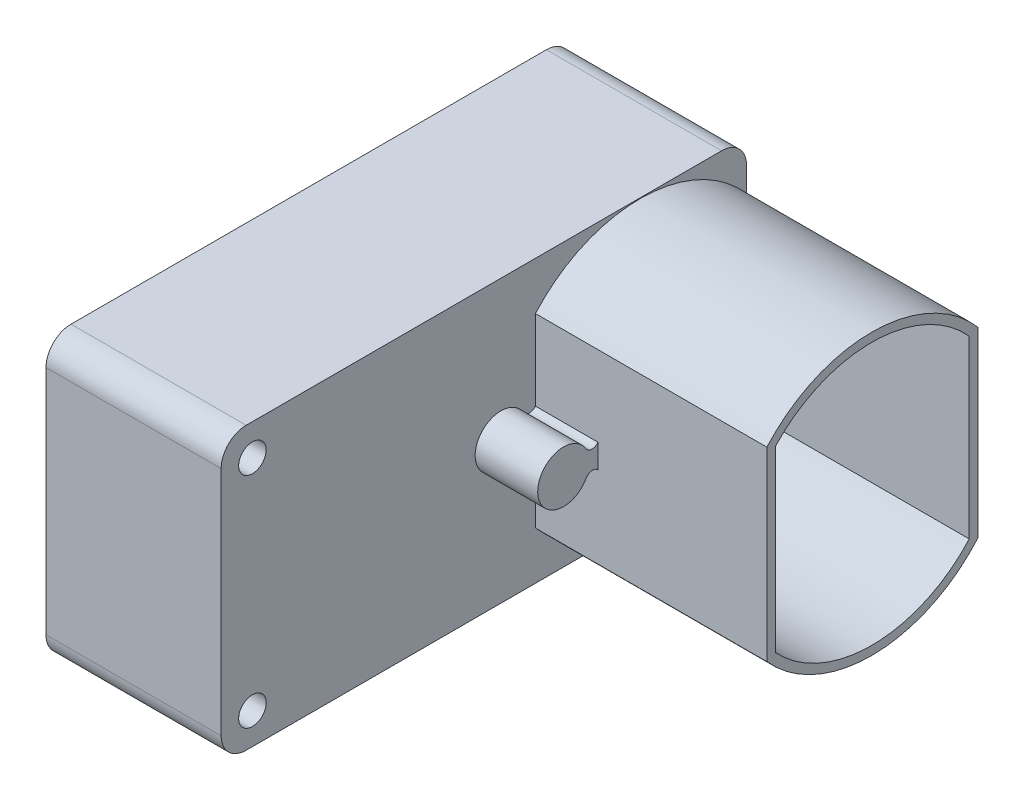
SolidWorks part; units mm, degrees
ref_plane "Front Plane" through (0, 0, 0) normal (0, 0, 1) x (1, 0, 0)
ref_plane "Top Plane" through (0, 0, 0) normal (0, 1, 0) x (1, 0, 0)
ref_plane "Right Plane" through (0, 0, 0) normal (1, 0, 0) x (0, 0, -1)
sketch "Sketch1" plane through (0, 0, 0) normal (0, 1, 0) x (1, 0, 0)
  line L1 (-21.7296, 20.5432) -> (-7.7296, 20.5432)
  line L2 (-21.7296, 20.5432) -> (-21.7296, -21.4568)
  line L3 (-21.7296, -21.4568) -> (-7.7296, -21.4568)
  line L4 (-7.7296, 20.5432) -> (-7.7296, -21.4568)
  dimension "D1" = 42
  dimension "D2" = 14
extrude "Boss-Extrude1" add sketch "Sketch1" along normal blind 22.5
fillet "Fillet1" radius 2 4 edges at (-14.7296, 22.5, -20.5432) (-14.7296, 0, -20.5432) (-14.7296, 0, 21.4568) (-14.7296, 22.5, 21.4568)
sketch "Sketch2" plane through (-7.7296, 0, 0) normal (1, 0, 0) x (0, 0, -1)
  line L0 (-19.4568, 0) -> (18.5432, 0) construction
  line L2 (3.6661, 18.6743) -> (3.6661, 3.8257)
  line L4 (20.5432, 18.5333) -> (20.5432, 3.9667)
  line L5 (20.5432, 20.5) -> (20.5432, 2) construction
  line L6 (-996.4568, 11.25) -> (49003.5432, 11.25) construction
  line L7 (12.0432, -977.25) -> (12.0432, 49022.75) construction
  arc A0 (20.5432, 18.5333) -> (3.6661, 18.6743) centre (12.0432, 11.25) ccw
  arc A1 (3.6661, 3.8257) -> (20.5432, 3.9667) centre (12.0432, 11.25) ccw
  point P11 (3.6661, 11.25)
  dimension "D1" = 11.25
extrude "Boss-Extrude2" add sketch "Sketch2" along normal blind 18.5
sketch "Sketch3" plane through (-7.7296, 0, 0) normal (1, 0, 0) x (0, 0, -1)
  line L0 (3.6661, 11.25) -> (-4.3884, 11.25) construction
  line L1 (3.6661, 18.6743) -> (3.6661, 3.8257) construction
  line L2 (3.6661, 18.6743) -> (3.6661, 3.8257) construction
  line L3 (3.6661, 12.2654) -> (3.6661, 10.3412)
  arc A0 (2.6785, 12.3299) -> (2.7239, 10.2481) centre (0.9148, 11.25) ccw
  arc A1 (2.6785, 12.3299) -> (3.6661, 12.2654) centre (3.1938, 12.6278) ccw
  arc A2 (2.7239, 10.2481) -> (3.6661, 10.3412) centre (3.2261, 9.9798) cw
  dimension "D1" = 2.7513
  dimension "D2" = 2.068
  dimension "D3" = 0.5953
  dimension "D4" = 0.5694
  dimension "D5" = 0.44
  dimension "D6" = 1.2702
  dimension "D7" = 1.3778
  dimension "D8" = 0.4723
extrude "Boss-Extrude3" add sketch "Sketch3" along normal blind 5
sketch "Sketch4" plane through (-7.7296, 0, 0) normal (1, 0, 0) x (0, 0, -1)
  line L0 (-18.9568, -979.1157) -> (-18.9568, 49020.8843) construction
  line L1 (-19.4568, 22.5) -> (18.5432, 22.5) construction
  line L2 (-21.4568, 20.5) -> (-21.4568, 2) construction
  line L3 (-19.4568, 0) -> (18.5432, 0) construction
  circle A0 centre (-18.9568, 20) radius 1.1
  circle A1 centre (-18.9568, 2.5) radius 1.1
  dimension "D1" = 2.5
  dimension "D2" = 2.5
  dimension "D3" = 2.5
extrude "Cut-Extrude1" cut sketch "Sketch4" against normal blind 15
sketch "Sketch5" plane through (0, 0, -20.5432) normal (0, 0, -1) x (-1, 0, 0)
  line L0 (7.7296, 18.5333) -> (7.7296, 3.9667) construction
  line L1 (21.7296, 0) -> (7.7296, 0) construction
  line L2 (6.7296, 9.25) -> (8.7296, 9.25)
  line L3 (6.7296, 9.25) -> (6.7296, 13.25)
  line L4 (6.7296, 13.25) -> (8.7296, 13.25)
  line L5 (8.7296, 9.25) -> (8.7296, 13.25)
  line L6 (6.7296, 9.25) -> (8.7296, 13.25) construction
  line L7 (6.7296, 13.25) -> (8.7296, 9.25) construction
  point P4 (7.7296, 11.25)
  dimension "D1" = 2
  dimension "D2" = 4
extrude "Boss-Extrude4" add sketch "Sketch5" along normal blind 5
sketch "Sketch6" plane through (-6.7296, 0, 0) normal (1, 0, 0) x (0, 0, -1)
  line L0 (25.5432, 13.25) -> (25.5432, 9.25) construction
  line L1 (20.5432, 3.9667) -> (20.5432, 18.5333) construction
  line L2 (20.5432, 13.25) -> (20.5432, 9.25) construction
  line L3 (25.5432, 9.25) -> (20.5432, 9.25) construction
  circle A0 centre (23.5432, 11.25) radius 2
  arc A1 (21.6793, 11.9753) -> (20.5432, 12.2253) centre (21.1327, 12.1978) cw
  arc A2 (21.6793, 10.5247) -> (20.5432, 10.7747) centre (21.0655, 10.4419) ccw
  line M1 (20.5432, 13.25) -> (20.5432, 9.25)
  dimension "D1" = 4
  dimension "D2" = 2
extrude "Boss-Extrude5" add sketch "Sketch6" along normal up to vertex (4 mm away) contours A0 A1 | A2 A0 A1 M1
sketch "Sketch7" plane through (-6.7296, 0, 0) normal (1, 0, 0) x (0, 0, -1)
  line L0 (23.5432, 13.25) -> (23.5432, 13.9672)
  line L1 (23.5432, 13.9672) -> (25.7602, 13.9672)
  line L2 (25.7602, 13.9672) -> (25.7602, 8.9705)
  line L3 (25.7602, 8.9705) -> (23.5432, 8.9705)
  line L4 (23.5432, 8.9705) -> (23.5432, 9.25)
  arc A0 (23.5432, 13.25) -> (23.5432, 9.25) centre (23.5432, 11.25) cw
  arc A1 (21.6793, 10.5247) -> (21.6793, 11.9753) centre (23.5432, 11.25) ccw construction
  arc A2 (23.5432, 9.25) -> (25.5432, 11.25) centre (23.5432, 11.25) ccw construction
extrude "Cut-Extrude2" cut sketch "Sketch7" against normal blind 2
sketch "Sketch12" plane through (-21.7296, 0, 0) normal (-1, 0, 0) x (0, 0, 1)
  line L0 (21.4568, 11.25) -> (10.4568, 11.25) construction
  line L1 (21.4568, 20.5) -> (21.4568, 2) construction
  circle A0 centre (10.4568, 11.25) radius 3.5
  circle A1 centre (10.4568, 11.25) radius 3.0703
extrude "Boss-Extrude6" add sketch "Sketch12" along normal blind 1
sketch "Sketch14" plane through (-21.7296, 0, 0) normal (-1, 0, 0) x (0, 0, 1)
  line L0 (-18.5432, 0) -> (19.4568, 0) construction
  line L2 (21.4568, 20.5) -> (21.4568, 2) construction
  circle A0 centre (10.4568, 11.25) radius 3
  dimension "D1" = 6
  dimension "D2" = 11.25
  dimension "D3" = 11
extrude "Boss-Extrude7" add sketch "Sketch14" along normal blind 1
sketch "Sketch15" plane through (-22.7296, 0, 0) normal (-1, 0, 0) x (0, 0, 1)
  line L2 (8.8539, 8.7141) -> (8.8539, 13.7859)
  line L4 (12.0597, 8.7141) -> (12.0597, 13.7859)
  line L5 (8.8539, 8.7141) -> (12.0597, 13.7859) construction
  line L6 (8.8539, 13.7859) -> (12.0597, 8.7141) construction
  circle A0 centre (10.4568, 11.25) radius 3 construction
  circle A1 centre (10.4568, 11.25) radius 1
  arc A2 (8.8539, 8.7141) -> (12.0597, 8.7141) centre (10.4568, 11.25) ccw
  arc A3 (12.0597, 13.7859) -> (8.8539, 13.7859) centre (10.4568, 11.25) ccw
  point P0 (10.4568, 11.25)
  point P1 (10.4568, 11.25)
  dimension "D1" = 6
  dimension "D2" = 2
extrude "Boss-Extrude8" add sketch "Sketch15" along normal blind 7
sketch "Sketch16" plane through (-21.7296, 0, 0) normal (-1, 0, 0) x (0, 0, 1)
  line L0 (21.4568, 11.25) -> (-0.5432, 11.25) construction
  line L1 (21.4568, 20.5) -> (21.4568, 2) construction
  circle A0 centre (-0.5432, 11.25) radius 2
extrude "Boss-Extrude9" add sketch "Sketch16" along normal blind 1.5
sketch "Sketch17" plane through (10.7704, 0, 0) normal (1, 0, 0) x (0, 0, -1)
  line L6 (19.8432, 4.2304) -> (19.8432, 18.2696)
  line L7 (4.3661, 18.4039) -> (4.3661, 4.0961)
  line L8 (19.8432, 4.2304) -> (19.8432, 18.2696)
  line L9 (4.3661, 18.4039) -> (4.3661, 4.0961)
  arc A6 (4.3661, 4.0961) -> (19.8432, 4.2304) centre (12.0432, 11.25) ccw
  arc A7 (19.8432, 18.2696) -> (4.3661, 18.4039) centre (12.0432, 11.25) ccw
  arc A8 (4.3661, 4.0961) -> (19.8432, 4.2304) centre (12.0432, 11.25) ccw
  arc A9 (19.8432, 18.2696) -> (4.3661, 18.4039) centre (12.0432, 11.25) ccw
  dimension "D1" = 0.7
extrude "Cut-Extrude3" cut sketch "Sketch17" against normal up to surface (18.5 mm away) up to face at (-7.7296, 2.5, 17.8568)
